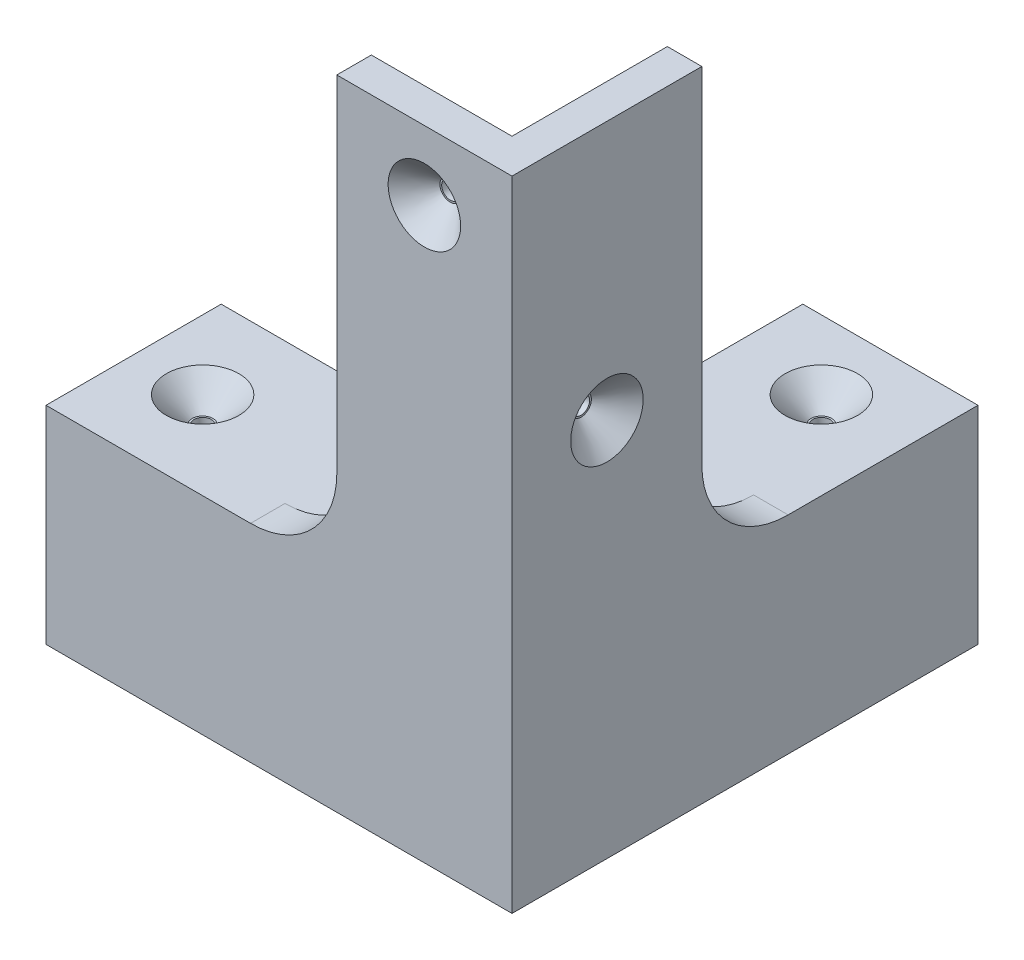
SolidWorks part; units mm, degrees
ref_plane "Front Plane" through (0, 0, 0) normal (0, 0, 1) x (1, 0, 0)
ref_plane "Top Plane" through (0, 0, 0) normal (0, 1, 0) x (1, 0, 0)
ref_plane "Right Plane" through (0, 0, 0) normal (1, 0, 0) x (0, 0, -1)
sketch "Sketch1" plane through (0, 0, 0) normal (0, 1, 0) x (1, 0, 0)
  line L1 (0, 0) -> (-54, 0)
  line L2 (0, 0) -> (0, 20.3)
  line L3 (0, 20.3) -> (-54, 20.3)
  line L4 (-54, 0) -> (-54, 20.3)
  line L5 (0, 0) -> (-20.3, 0)
  line L6 (0, 0) -> (0, 54)
  line L7 (0, 54) -> (-20.3, 54)
  line L8 (-20.3, 0) -> (-20.3, 54)
  point P8 (-20.3, 35.9378)
  dimension "D1" = 20.3
  dimension "D2" = 20.3
  dimension "D3" = 54
  dimension "D4" = 54
extrude "Boss-Extrude1" add sketch "Sketch1" against normal blind 24 contours L1 L8 L3 L4 | L8 L1 L2 L3 | L8 L3 L6 L7
shell "Shell1" thickness 4
sketch "Sketch2" plane through (0, 0, 0) normal (0, 1, 0) x (1, 0, 0)
  line L0 (-54, 10.15) -> (0, 10.15) construction
  line L1 (-54, 0) -> (-54, 20.3) construction
  line L2 (0, 0) -> (0, 54) construction
  line L3 (0, 10.15) -> (0, 54) construction
  line L4 (0, 54) -> (-10.15, 54) construction
  line L5 (0, 54) -> (-20.3, 54) construction
  line L6 (-10.15, 54) -> (-10.15, 0) construction
  line L7 (0, 0) -> (-54, 0) construction
  circle A0 centre (-10.15, 46) radius 1
  circle A1 centre (-46, 10.15) radius 1
  dimension "D1" = 2
  dimension "D2" = 2
  dimension "D3" = 8
  dimension "D4" = 8
extrude "Cut-Extrude1" cut sketch "Sketch2" against normal blind 24
sketch "Sketch3" plane through (0, 0, 0) normal (0, 1, 0) x (1, 0, 0)
  circle A0 centre (-46, 10.15) radius 4.2
  circle A1 centre (-10.15, 46) radius 4.2
  dimension "D1" = 8.4
  dimension "D2" = 8.4
extrude "Cut-Extrude2" cut sketch "Sketch3" against normal blind 3 draft 45
sketch "Sketch4" plane through (0, 0, 0) normal (0, 1, 0) x (1, 0, 0)
  line L1 (0, 0) -> (-20.3, 0)
  line L2 (0, 0) -> (0, 22)
  line L3 (0, 22) -> (-20.3, 22)
  line L4 (-20.3, 0) -> (-20.3, 22)
  line L5 (-20.3, 20.3) -> (-20.3, 54) construction
  point P5 (-20.3, 11)
  dimension "D1" = 22
extrude "Boss-Extrude2" add sketch "Sketch4" along normal blind 50 separate body
shell "Shell2" thickness 4
combine bodies "Combine1" operation type add bodies to combine 103 104
sketch "Sketch5" plane through (0, 0, 0) normal (0, 0, 1) x (1, 0, 0)
  line L0 (-20.3, 50) -> (0, 50) construction
  circle A0 centre (-10.15, 42) radius 1
  point P4 (-10.15, 50)
  dimension "D1" = 2
  dimension "D2" = 8
extrude "Cut-Extrude3" cut sketch "Sketch5" against normal up to next
sketch "Sketch6" plane through (0, 0, 0) normal (0, 0, 1) x (1, 0, 0)
  circle A0 centre (-10.15, 42) radius 4.2
  dimension "D1" = 8.4
extrude "Cut-Extrude4" cut sketch "Sketch6" against normal blind 3 draft 45
ref_plane "Plane1" through (0, 0, 0) normal (-0.7071, 0, 0.7071) x (0.7071, 0, 0.7071)
sketch "Sketch7" plane through (0, 0, 0) normal (1, 0, 0) x (0, 0, -1)
  line L0 (0, 50) -> (22, 50) construction
  circle A0 centre (11, 20) radius 1
  point P4 (11, 50)
  dimension "D1" = 2
  dimension "D2" = 30
extrude "Cut-Extrude5" cut sketch "Sketch7" against normal up to next
sketch "Sketch8" plane through (0, 0, 0) normal (1, 0, 0) x (0, 0, -1)
  circle A0 centre (11, 20) radius 4.2
  dimension "D1" = 8.4
extrude "Cut-Extrude6" cut sketch "Sketch8" against normal blind 3 draft 45
fillet "Fillet1" radius 10 2 edges at (-20.3, 0, -2) (-2, 0, -22)
equation "\"D2@Sketch1\"=\"D1@Sketch1\""
equation "\"D4@Sketch1\"=\"D3@Sketch1\""
equation "\"D2@Sketch2\"=\"D1@Sketch2\""
equation "\"D2@Sketch3\"=\"D1@Sketch3\""
